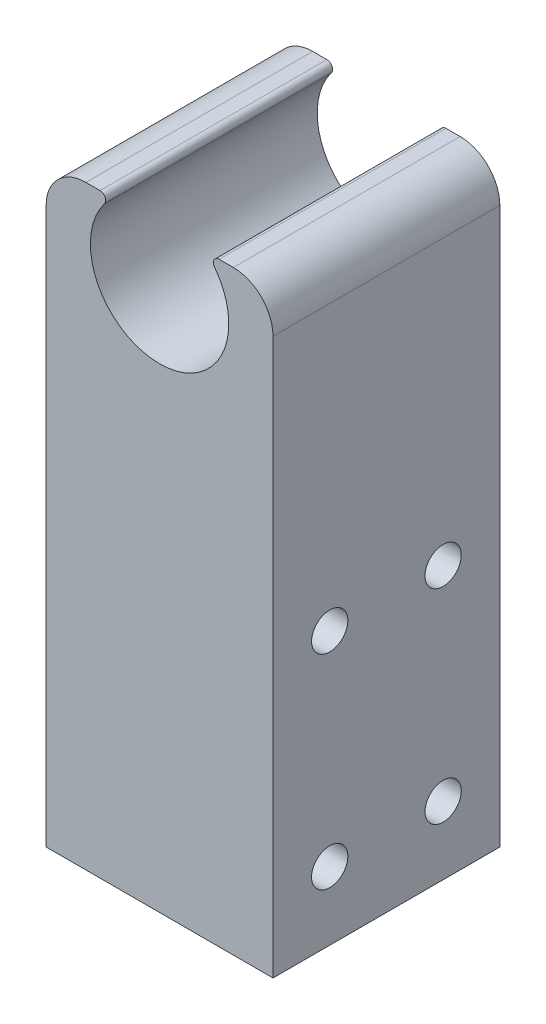
SolidWorks part; units mm, degrees
material "POM"
ref_plane "前视基准面" through (0, 0, 0) normal (0, 0, 1) x (1, 0, 0)
ref_plane "上视基准面" through (0, 0, 0) normal (0, 1, 0) x (1, 0, 0)
ref_plane "右视基准面" through (0, 0, 0) normal (1, 0, 0) x (0, 0, -1)
sketch "草图1" plane through (0, 0, 0) normal (0, 0, 1) x (1, 0, 0)
  line L0 (10, 0) -> (10, 30) construction
  line L1 (0, 0) -> (20, 0)
  line L2 (0, 0) -> (0, 30)
  line L3 (0, 30) -> (20, 30) construction
  line L4 (20, 0) -> (20, 30)
  line L5 (10, 48) -> (10, 30) construction
  line L6 (0, 30) -> (0, 52.5)
  line L7 (0, 52.5) -> (5.8817, 52.5)
  line L8 (20, 52.5) -> (14.1183, 52.5)
  line L10 (20, 30) -> (20, 52.5)
  arc A1 (5.8817, 52.5) -> (14.1183, 52.5) centre (10, 48) ccw
  dimension "D4" = 12.2
  dimension "D5" = 22.5
  dimension "D1" = 30
  dimension "D2" = 20
  dimension "D3" = 18
extrude "凸台-拉伸1" add sketch "草图1" along normal blind 20
sketch "草图2" plane through (20, 0, 0) normal (1, 0, 0) x (0, 0, -1)
  line L0 (-10, 58) -> (-10, 0) construction
  line L1 (-20, 52.5) -> (0, 52.5) construction
  line L2 (-20, 0) -> (0, 0) construction
  line L3 (-20, 15) -> (0, 15) construction
  line L4 (-20, 0) -> (-20, 52.5) construction
  line L5 (0, 0) -> (0, 52.5) construction
  circle A0 centre (-15, 24) radius 1.6
  circle A1 centre (-15, 6) radius 1.6
  circle A2 centre (-5, 6) radius 1.6
  circle A3 centre (-5, 24) radius 1.6
  circle A4 centre (-10, 37.5) radius 1.6 construction
  dimension "D2" = 3.2
  dimension "D3" = 10
  dimension "D4" = 18
  dimension "D5" = 15
  dimension "D1" = 15
extrude "切除-拉伸1" cut sketch "草图2" against normal through all
fillet "圆角1" radius 3.5 2 edges at (20, 52.5, 10) (0, 52.5, 10)
fillet "圆角2" radius 0.5 2 edges at (14.1183, 52.5, 10) (5.8817, 52.5, 10)
